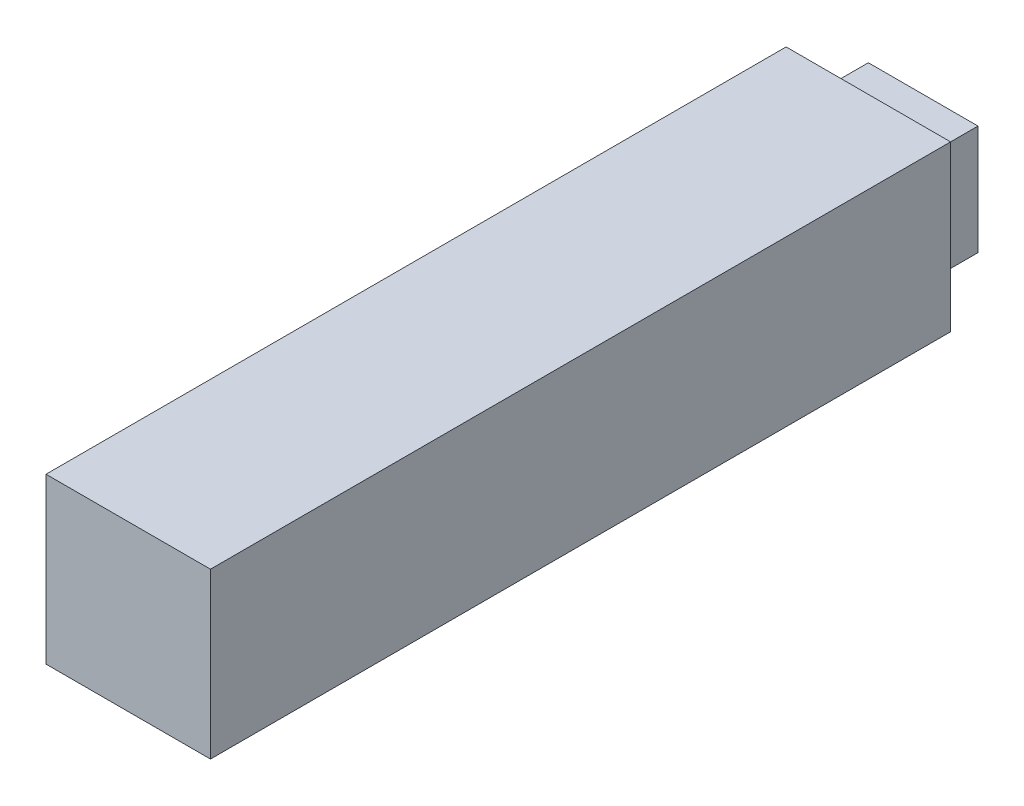
SolidWorks part; units mm, degrees
ref_plane "Front Plane" through (0, 0, 0) normal (0, 0, 1) x (1, 0, 0)
ref_plane "Top Plane" through (0, 0, 0) normal (0, 1, 0) x (1, 0, 0)
ref_plane "Right Plane" through (0, 0, 0) normal (1, 0, 0) x (0, 0, -1)
sketch "Sketch1" plane through (0, 0, 0) normal (0, 0, 1) x (1, 0, 0)
  line L1 (-15, -15) -> (15, -15)
  line L2 (-15, -15) -> (-15, 15)
  line L3 (-15, 15) -> (15, 15)
  line L4 (15, -15) -> (15, 15)
extrude "Boss-Extrude1" add sketch "Sketch1" along normal blind 135
sketch "Sketch2" plane through (0, 0, 0) normal (0, 0, 1) x (1, 0, 0)
  line L1 (-10, -10) -> (10, -10)
  line L2 (-10, -10) -> (-10, 10)
  line L3 (-10, 10) -> (10, 10)
  line L4 (10, -10) -> (10, 10)
extrude "Boss-Extrude2" add sketch "Sketch2" against normal blind 10
sketch "Sketch3" plane through (-15, 0, 0) normal (-1, 0, 0) x (0, 0, 1)
  line L0 (109.75, -10.25) -> (130.25, -10.25)
  line L1 (130.25, -10.25) -> (130.25, 10.25)
  line L2 (130.25, 10.25) -> (109.75, 10.25)
  line L3 (109.75, 10.25) -> (109.75, -10.25)
extrude "Cut-Extrude2" cut sketch "Sketch3" against normal blind 15
sketch "Sketch4" plane through (0, -15, 0) normal (0, -1, 0) x (1, 0, 0)
  line L0 (-10.25, 109.75) -> (10.25, 109.75)
  line L1 (10.25, 109.75) -> (10.25, 130.25)
  line L2 (10.25, 130.25) -> (-10.25, 130.25)
  line L3 (-10.25, 130.25) -> (-10.25, 109.75)
extrude "Cut-Extrude4" cut sketch "Sketch4" against normal blind 15
